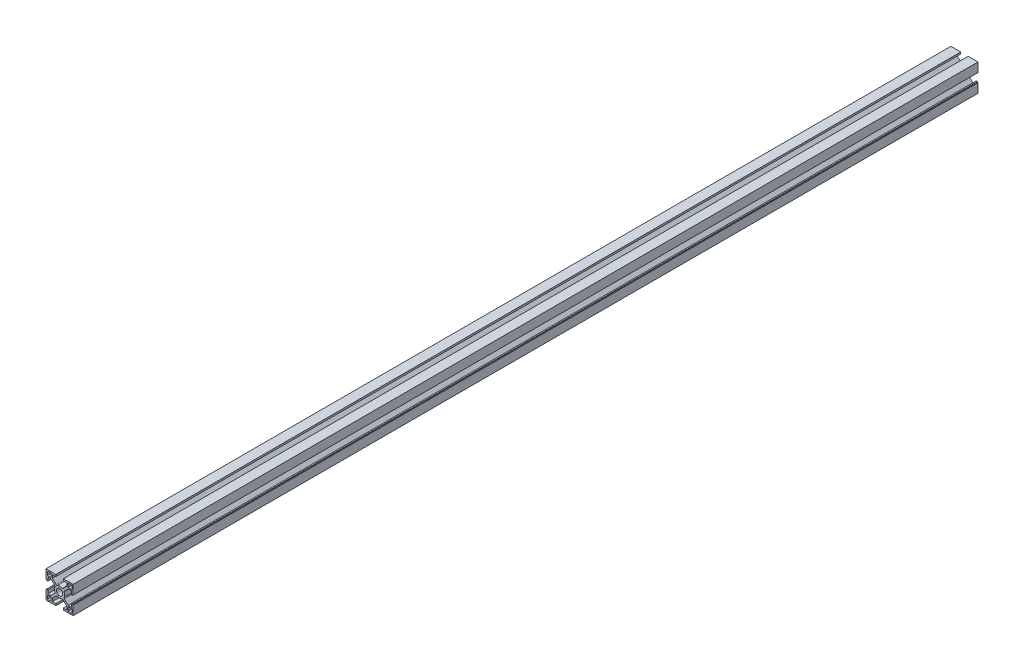
SolidWorks part; units mm, degrees
material "6063-O"
ref_plane "Front Plane" through (0, 0, 0) normal (0, 0, 1) x (1, 0, 0)
ref_plane "Top Plane" through (0, 0, 0) normal (0, 1, 0) x (1, 0, 0)
ref_plane "Right Plane" through (0, 0, 0) normal (1, 0, 0) x (0, 0, -1)
sketch "Sketch1" plane through (0, 0, 0) normal (0, 0, 1) x (1, 0, 0)
  line L0 (-13, 8) -> (-9.5556, 8)
  line L1 (-15, -15) -> (-4.1, -15)
  line L2 (-15, -15) -> (-15, -4.8)
  line L3 (-15, 15) -> (-4.1, 15)
  line L4 (15, -15) -> (15, -4.8)
  line L5 (-15, -15) -> (15, 15) construction
  line L6 (-15, 15) -> (15, -15) construction
  line L7 (-8, 9.5556) -> (-8, 13)
  line L8 (-8, 9.5556) -> (-3.7211, 5.2767)
  line L9 (-9.5556, 8) -> (-5.2767, 3.7211)
  line L10 (13.5, 13.5) -> (13.5, 9.25)
  line L11 (-13.5, -9.25) -> (-9.25, -9.25)
  line L12 (-13, -8) -> (-13, -4.1)
  line L13 (13, 8) -> (9.5556, 8)
  line L14 (8, 13) -> (8, 9.5556)
  line L15 (-14.3, -4.1) -> (-13, -4.1)
  line L16 (15, 4.8) -> (15, 15)
  line L17 (13, -8) -> (9.5556, -8)
  line L18 (8, -13) -> (8, -9.5556)
  line L19 (-14.3, 4.1) -> (-13, 4.1)
  line L20 (15, -15) -> (15, 15) construction
  line L21 (-13, -8) -> (-9.5556, -8)
  line L22 (-8, -13) -> (-8, -9.5556)
  line L23 (4.1, 15) -> (15, 15)
  line L24 (13, 4.1) -> (13, 8)
  line L25 (14.3, -4.1) -> (13, -4.1)
  line L26 (3.7211, 5.2767) -> (8, 9.5556)
  line L27 (14.3, 4.1) -> (13, 4.1)
  line L28 (-15, 15) -> (15, 15) construction
  line L29 (4.1, 13) -> (8, 13)
  line L30 (-13, 13) -> (13, 13) construction
  line L31 (3.7211, -5.2767) -> (8, -9.5556)
  line L32 (-4.1, 15) -> (-4.1, 13)
  line L33 (4.1, -13) -> (8, -13)
  line L34 (4.1, 15) -> (4.1, 13)
  line L35 (-13, -13) -> (13, -13) construction
  line L36 (5.2767, -3.7211) -> (9.5556, -8)
  line L37 (5.2767, 3.7211) -> (9.5556, 8)
  line L38 (-4.1, -13) -> (-4.1, -15)
  line L39 (-9.5556, -8) -> (-4.7326, -3.1769)
  line L40 (4.1, -13) -> (4.1, -15)
  line L41 (-8, -9.5556) -> (-3.7211, -5.2767)
  line L42 (-13.5, -9.25) -> (-13.5, -13.5)
  line L43 (-8, 13) -> (-4.1, 13)
  line L44 (13, -8) -> (13, -4.1)
  line L45 (-8, -13) -> (-4.1, -13)
  line L46 (-15, 4.8) -> (-15, 15)
  line L47 (-15, -15) -> (-15, 15) construction
  line L48 (13, -13) -> (13, 13) construction
  line L49 (-13, 4.1) -> (-13, 8)
  line L50 (-13, -13) -> (-13, 13) construction
  line L51 (4.1, -15) -> (15, -15)
  line L52 (-15, -15) -> (15, -15) construction
  line L53 (-13.5, -13.5) -> (-9.25, -13.5)
  line L54 (-9.25, -9.25) -> (-9.25, -13.5)
  line L55 (9.25, 9.25) -> (13.5, 9.25)
  line L56 (9.25, 13.5) -> (13.5, 13.5)
  line L57 (9.25, 13.5) -> (9.25, 9.25)
  line L58 (13.5, -13.5) -> (9.25, -13.5)
  line L59 (-9.25, 13.5) -> (-13.5, 13.5)
  line L60 (-9.25, 13.5) -> (-9.25, 9.25)
  line L61 (-9.25, 9.25) -> (-13.5, 9.25)
  line L62 (-13.5, 13.5) -> (-13.5, 9.25)
  line L63 (13.5, -9.25) -> (13.5, -13.5)
  line L64 (13.5, -9.25) -> (9.25, -9.25)
  line L65 (9.25, -9.25) -> (9.25, -13.5)
  line L69 (15, -4.8) -> (14.3, -4.8)
  line L70 (14.3, -4.1) -> (14.3, -4.8)
  line L73 (15, 4.8) -> (14.3, 4.8)
  line L74 (14.3, 4.1) -> (14.3, 4.8)
  line L77 (-15, -4.8) -> (-14.3, -4.8)
  line L78 (-14.3, -4.1) -> (-14.3, -4.8)
  line L81 (-15, 4.8) -> (-14.3, 4.8)
  line L82 (-14.3, 4.1) -> (-14.3, 4.8)
  circle A0 centre (0, 0) radius 3.5
  arc A1 (2.5641, 5.0907) -> (-2.5641, 5.0907) centre (0, 0) ccw
  arc A2 (5.0907, -2.5641) -> (5.0907, 2.5641) centre (0, 0) ccw
  arc A3 (-2.5641, -5.0907) -> (2.5641, -5.0907) centre (0, 0) ccw
  arc A4 (-5.0907, 2.5641) -> (-4.7326, -3.1769) centre (0, 0) ccw
  arc A5 (-5.2767, 3.7211) -> (-5.0907, 2.5641) centre (-5.9838, 3.014) cw
  arc A6 (-3.7211, 5.2767) -> (-2.5641, 5.0907) centre (-3.014, 5.9838) ccw
  arc A7 (5.2767, 3.7211) -> (5.0907, 2.5641) centre (5.9838, 3.014) ccw
  arc A8 (3.7211, 5.2767) -> (2.5641, 5.0907) centre (3.014, 5.9838) cw
  arc A9 (5.2767, -3.7211) -> (5.0907, -2.5641) centre (5.9838, -3.014) cw
  arc A10 (3.7211, -5.2767) -> (2.5641, -5.0907) centre (3.014, -5.9838) ccw
  arc A11 (-3.7211, -5.2767) -> (-2.5641, -5.0907) centre (-3.014, -5.9838) cw
  point P0 (0, 0)
  point P29 (-15, 0)
  point P34 (15, 0)
  point P39 (0, 15)
  point P44 (0, -15)
  point P55 (-4.7326, 3.1769)
  point P91 (4.7326, -3.1769)
  point P96 (-3.1769, -4.7326)
  dimension "D1" = 7
  dimension "D2" = 11.4
  dimension "D34" = 1
  dimension "D3" = 30
  dimension "D4" = 30
  dimension "D5" = 7
  dimension "D6" = 7
  dimension "D7" = 7
  dimension "D8" = 7
  dimension "D9" = 1.5
  dimension "D10" = 1.5
  dimension "D11" = 4.25
  dimension "D12" = 4.25
  dimension "D13" = 4.25
  dimension "D14" = 8.2
  dimension "D15" = 4.25
  dimension "D16" = 1.5
  dimension "D18" = 10.9
  dimension "D19" = 10.9
  dimension "D20" = 10.9
  dimension "D21" = 10.9
  dimension "D22" = 10.9
  dimension "D23" = 10.9
  dimension "D24" = 10.9
  dimension "D25" = 1.5
  dimension "D26" = 0.7
  dimension "D27" = 0.7
  dimension "D28" = 0.7
  dimension "D29" = 0.7
  dimension "D30" = 0.7
  dimension "D31" = 0.7
  dimension "D32" = 0.7
  dimension "D33" = 0.7
  dimension "D17" = 2
extrude "Boss-Extrude1" add sketch "Sketch1" along normal mid plane 1000
